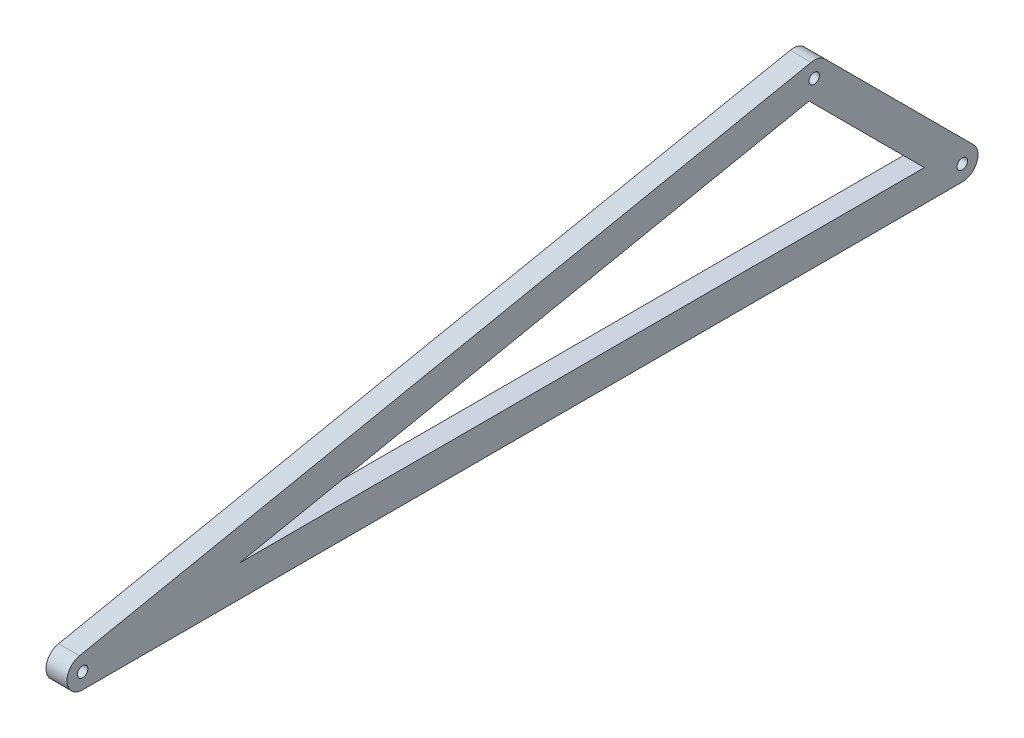
SolidWorks part; units mm, degrees
material "AISI 304"
ref_plane "前视基准面" through (0, 0, 0) normal (0, 0, 1) x (1, 0, 0)
ref_plane "上视基准面" through (0, 0, 0) normal (0, 1, 0) x (1, 0, 0)
ref_plane "右视基准面" through (0, 0, 0) normal (1, 0, 0) x (0, 0, -1)
sketch "草图1" plane through (0, 0, 0) normal (1, 0, 0) x (0, 0, -1)
  line L0 (-8.7467, 4.5229) -> (75.2533, 4.5229)
  line L1 (-8.7467, 1.5229) -> (75.2533, 1.5229)
  circle A0 centre (-8.7467, 3.0229) radius 0.5
  arc A1 (-8.7467, 4.5229) -> (-8.7467, 1.5229) centre (-8.7467, 3.0229) ccw
  circle A2 centre (75.2533, 3.0229) radius 0.5
  arc A3 (75.2533, 1.5229) -> (75.2533, 4.5229) centre (75.2533, 3.0229) ccw
  dimension "D1" = 1
  dimension "D2" = 3
  dimension "D3" = 84
extrude "凸台-拉伸1" add sketch "草图1" along normal blind 2
sketch "草图2" plane through (0, 0, 0) normal (-1, 0, 0) x (0, 0, 1)
  line L1 (-62.1718, 18.2257) -> (-76.314, 4.0835)
  line L2 (-60.8135, 18.6352) -> (9.0443, 4.493)
  line L3 (-74.1926, 1.9622) -> (-60.6198, 15.5351)
  line L4 (-60.6198, 15.5351) -> (8.4491, 1.5527)
  circle A0 centre (-61.1112, 17.165) radius 0.5
  arc A1 (-60.8135, 18.6352) -> (-62.1718, 18.2257) centre (-61.1112, 17.165) ccw
  arc A2 (-75.2533, 4.5229) -> (-75.2533, 1.5229) centre (-75.2533, 3.0229) ccw construction
  circle A3 centre (-75.2533, 3.0229) radius 0.5 construction
  arc A4 (8.7467, 1.5229) -> (8.7467, 4.5229) centre (8.7467, 3.0229) ccw construction
  arc A5 (-76.314, 4.0835) -> (-74.1926, 1.9622) centre (-75.2533, 3.0229) ccw
  arc A6 (8.4491, 1.5527) -> (9.0443, 4.493) centre (8.7467, 3.0229) ccw
  circle A7 centre (-75.2533, 3.0229) radius 0.5
  circle A8 centre (8.7467, 3.0229) radius 0.5
  dimension "D1" = 20
extrude "凸台-拉伸2" add sketch "草图2" against normal up to surface (2 mm away) up to face at (2, 3.0229, 8.2467)
